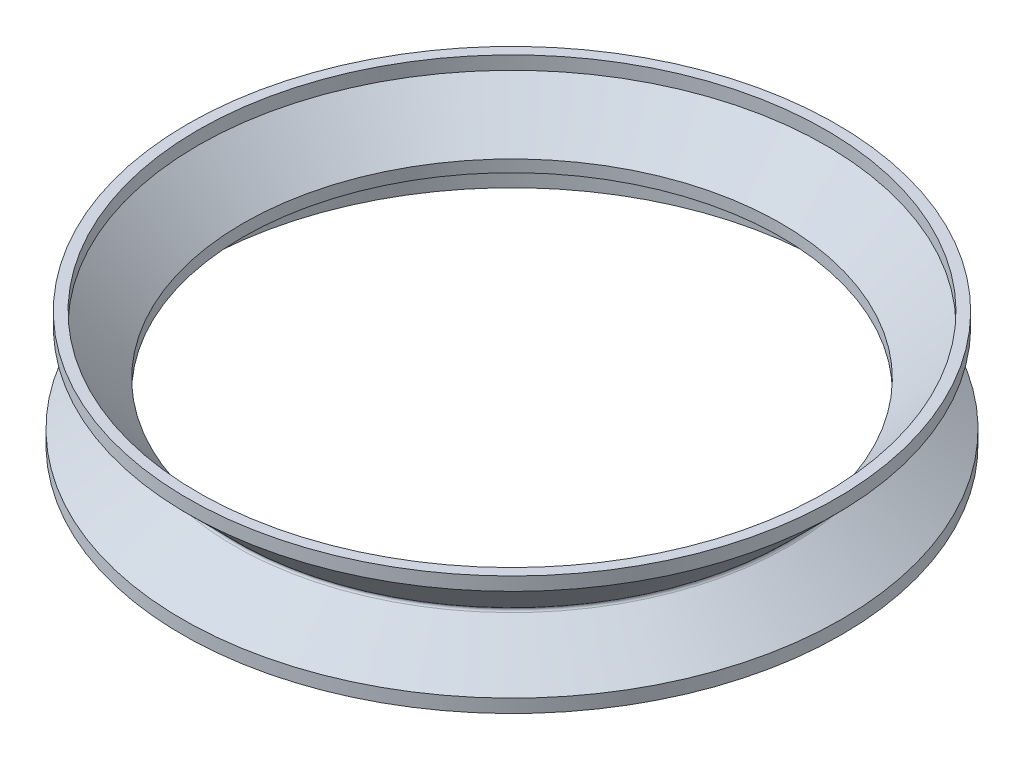
SolidWorks part; units mm, degrees
ref_plane "Front Plane" through (0, 0, 0) normal (0, 0, 1) x (1, 0, 0)
ref_plane "Top Plane" through (0, 0, 0) normal (0, 1, 0) x (1, 0, 0)
ref_plane "Right Plane" through (0, 0, 0) normal (1, 0, 0) x (0, 0, -1)
sketch "Sketch1" plane through (0, 0, 0) normal (0, 0, 1) x (1, 0, 0)
  line L0 (-42.6436, 0) -> (43.9692, 0) construction
  line L1 (0.6628, 0) -> (-6.8372, 7.5)
  line L2 (0.6628, 0) -> (-7.6205, -5.8)
  line L3 (1.4628, -1.0268) -> (-5.354, -5.8)
  line L5 (-6.8372, 7.5) -> (-5.2816, 7.5)
  line L6 (-7.6205, -5.8) -> (-5.354, -5.8)
  line L7 (41.7784, 7.109) -> (41.7784, -8.109) construction
  line L8 (2.6775, -0.1763) -> (-14.7461, 17.2473) construction
  line L9 (0.6628, 0) -> (-15.6653, 16.3281) construction
  line L10 (0.6628, 0) -> (-16.9771, -12.3516) construction
  line L11 (2.6775, -0.1763) -> (-16.2314, -13.4165) construction
  line L12 (0.6628, 0) -> (2.2628, 0) construction
  line L13 (1.4628, -1.0268) -> (1.4628, 0.7556)
  line L14 (1.4628, 0.7556) -> (-5.2816, 7.5)
  point P11 (1.4628, 0)
  dimension "D1" = 45
  dimension "D2" = 35
  dimension "D4" = 7.5
  dimension "D5" = 5.8
  dimension "D6" = 47.06
  dimension "D7" = 1.6
  dimension "D8" = 1.1
  dimension "D3" = 1.3
revolve "Revolve1" add sketch "Sketch1" angle 360 about L7
scale "Scale1" [suppressed]
fillet "Fillet2" radius 0.4 1 edges at (0.6628, 0, 0)
sketch "Sketch2" plane through (0, 7.5, 0) normal (0, 1, 0) x (1, 0, 0)
  circle A0 centre (41.7784, 0) radius 48.6156 construction
  circle A1 centre (41.7784, 0) radius 47.06 construction
  circle A2 centre (41.7784, 0) radius 48.6156
  circle A3 centre (41.7784, 0) radius 47.06
extrude "Boss-Extrude1" add sketch "Sketch2" along normal blind 2
sketch "Sketch3" plane through (0, -5.8, 0) normal (0, -1, 0) x (1, 0, 0)
  circle A0 centre (41.7784, 0) radius 47.1324 construction
  circle A1 centre (41.7784, 0) radius 49.3989 construction
  circle A2 centre (41.7784, 0) radius 47.1324
  circle A3 centre (41.7784, 0) radius 49.3989
extrude "Boss-Extrude2" add sketch "Sketch3" along normal blind 2
